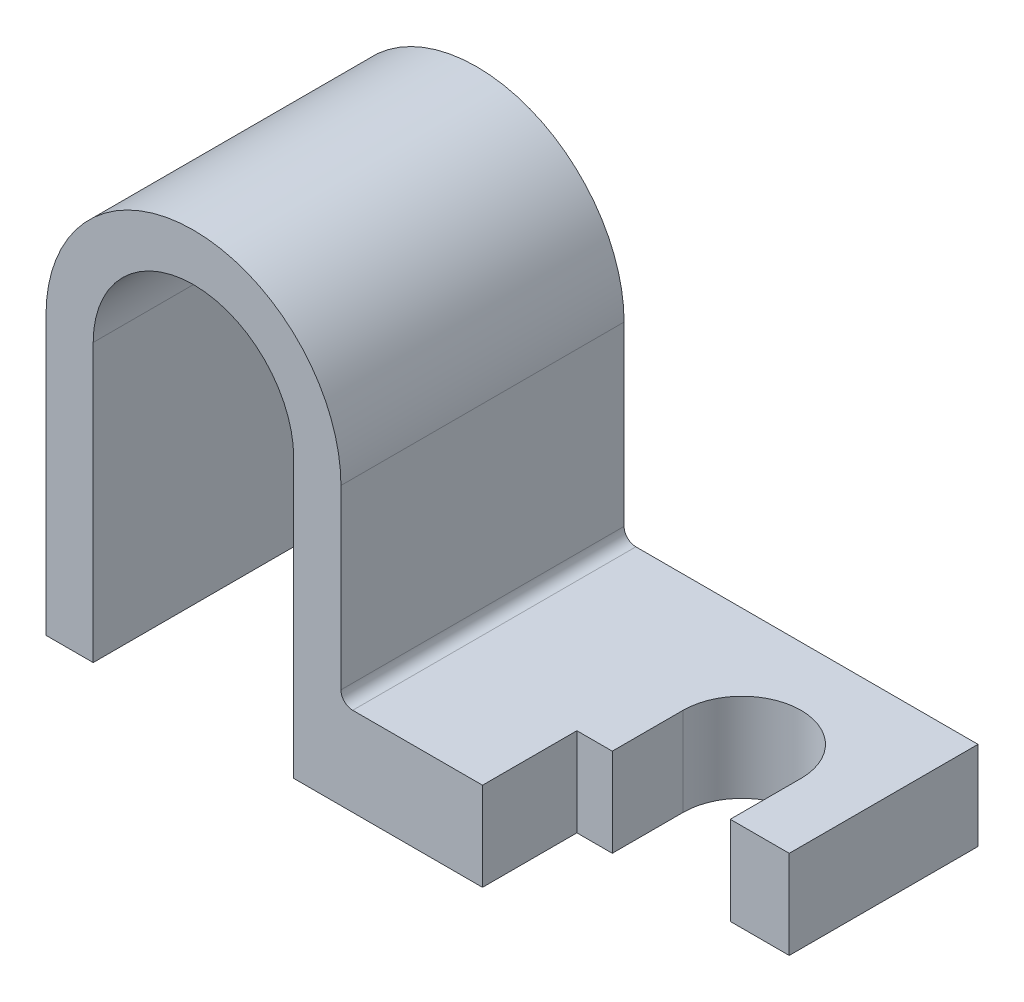
SolidWorks part; units mm, degrees
ref_plane "前基準面" through (0, 0, 0) normal (0, 0, 1) x (1, 0, 0)
ref_plane "上基準面" through (0, 0, 0) normal (0, 1, 0) x (1, 0, 0)
ref_plane "右基準面" through (0, 0, 0) normal (1, 0, 0) x (0, 0, -1)
sketch "草圖1" plane through (0, 0, 0) normal (0, 0, 1) x (1, 0, 0)
  line L0 (0, 0) -> (8, 0)
  line L1 (8, 0) -> (8, 47)
  line L2 (42, 47) -> (42, 0)
  line L3 (42, 0) -> (110, 0)
  line L4 (110, 0) -> (110, 15)
  line L5 (110, 15) -> (50, 15)
  line L6 (50, 15) -> (50, 47)
  line L7 (0, 47) -> (0, 0)
  arc A0 (8, 47) -> (42, 47) centre (25, 47) cw
  arc A1 (50, 47) -> (0, 47) centre (25, 47) ccw
  dimension "D2" = 34
  dimension "D3" = 25
  dimension "D1" = 47
  dimension "D4" = 110
  dimension "D5" = 15
extrude "填料-伸長1" add sketch "草圖1" against normal blind 48
sketch "草圖2" plane through (0, 15, 0) normal (0, 1, 0) x (1, 0, 0)
  line L0 (74, 0) -> (74, 16)
  line L1 (110, 0) -> (50, 0) construction
  line L2 (74, 16) -> (80, 16)
  line L3 (80, 16) -> (80, 28)
  line L4 (100, 28) -> (100, 16)
  line L5 (100, 16) -> (110, 16)
  line L6 (110, 48) -> (110, 0) construction
  line L7 (110, 16) -> (110, 0)
  line L8 (110, 0) -> (74, 0)
  arc A0 (80, 28) -> (100, 28) centre (90, 28) cw
  dimension "D5" = 16
  dimension "D6" = 28
  dimension "D1" = 10
  dimension "D2" = 16
  dimension "D3" = 36
  dimension "D4" = 6
extrude "除料-伸長1" cut sketch "草圖2" against normal blind 48
fillet "圓角1" radius 2 1 edges at (50, 15, -24)
